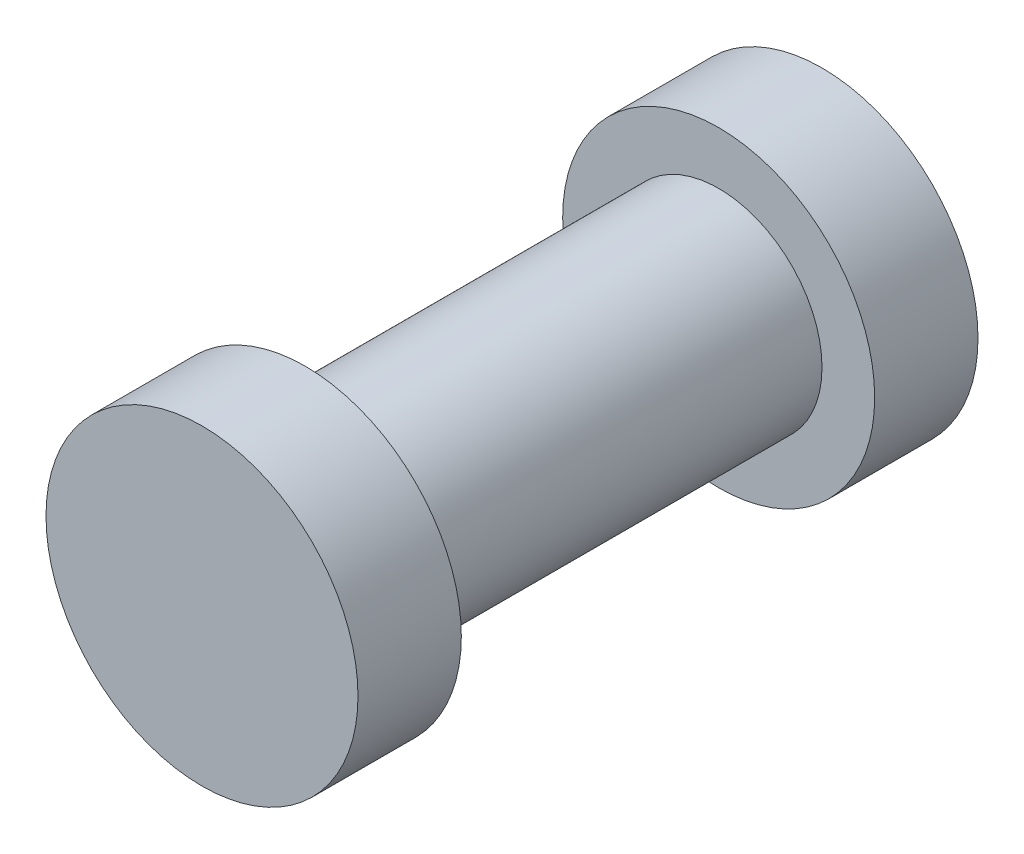
SolidWorks part; units mm, degrees
ref_plane "Front Plane" through (0, 0, 0) normal (0, 0, 1) x (1, 0, 0)
ref_plane "Top Plane" through (0, 0, 0) normal (0, 1, 0) x (1, 0, 0)
ref_plane "Right Plane" through (0, 0, 0) normal (1, 0, 0) x (0, 0, -1)
sketch "Sketch2" plane through (0, 0, 0) normal (0, 0, 1) x (1, 0, 0)
  circle A0 centre (0, 0) radius 5
  dimension "D1" = 10
extrude "Boss-Extrude1" add sketch "Sketch2" along normal mid plane 20
sketch "Sketch3" plane through (0, 0, 10) normal (0, 0, 1) x (1, 0, 0)
  circle A0 centre (0, 0) radius 7.5483
extrude "Boss-Extrude2" add sketch "Sketch3" along normal blind 5
sketch "Sketch4" plane through (0, 0, -10) normal (0, 0, -1) x (-1, 0, 0)
  circle A0 centre (0, 0) radius 7.5483
extrude "Boss-Extrude3" add sketch "Sketch4" along normal blind 5
